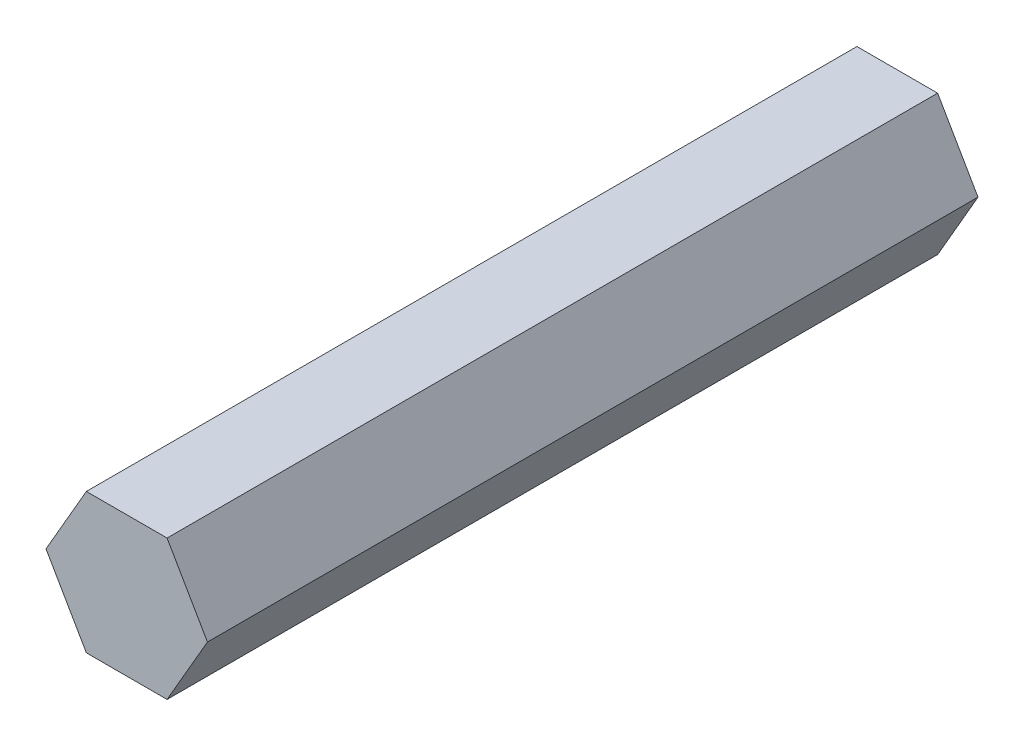
SolidWorks part; units mm, degrees
ref_plane "Front Plane" through (0, 0, 0) normal (0, 0, 1) x (1, 0, 0)
ref_plane "Top Plane" through (0, 0, 0) normal (0, 1, 0) x (1, 0, 0)
ref_plane "Right Plane" through (0, 0, 0) normal (1, 0, 0) x (0, 0, -1)
sketch "Sketch1" plane through (0, 0, 0) normal (0, 0, 1) x (1, 0, 0)
  line L1 (7.3323, 0) -> (3.6662, 6.35)
  line L2 (3.6662, 6.35) -> (-3.6662, 6.35)
  line L3 (-3.6662, 6.35) -> (-7.3323, 0)
  line L4 (-7.3323, 0) -> (-3.6662, -6.35)
  line L5 (-3.6662, -6.35) -> (3.6662, -6.35)
  line L6 (3.6662, -6.35) -> (7.3323, 0)
  circle A0 centre (0, 0) radius 6.35 construction
  dimension "D1" = 12.7
extrude "Boss-Extrude1" add sketch "Sketch1" along normal blind 70
